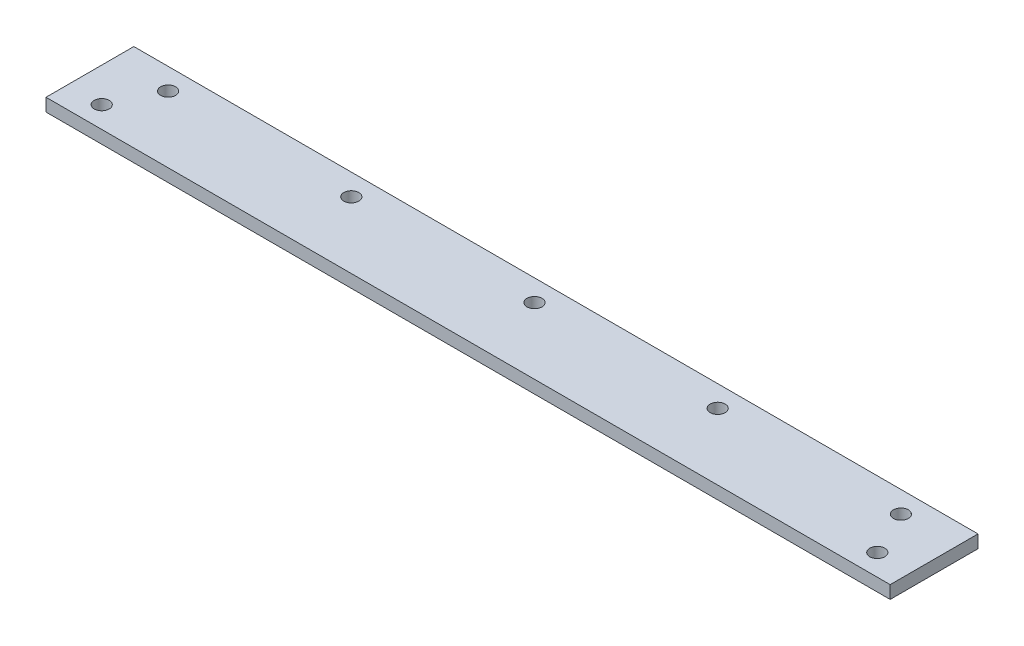
SolidWorks part; units mm, degrees
ref_plane "前视基准面" through (0, 0, 0) normal (0, 0, 1) x (1, 0, 0)
ref_plane "上视基准面" through (0, 0, 0) normal (0, 1, 0) x (1, 0, 0)
ref_plane "右视基准面" through (0, 0, 0) normal (1, 0, 0) x (0, 0, -1)
sketch "草图1" plane through (0, 0, 0) normal (0, 1, 0) x (1, 0, 0)
  line L1 (0, 0) -> (197, 0)
  line L2 (0, 0) -> (0, 20.5)
  line L3 (0, 20.5) -> (197, 20.5)
  line L4 (197, 0) -> (197, 20.5)
  dimension "D1" = 197
  dimension "D2" = 20.5
extrude "凸台-拉伸1" add sketch "草图1" along normal blind 3
sketch "草图2" plane through (0, 3, 0) normal (0, 1, 0) x (1, 0, 0)
  line L0 (13, 10) -> (3, 10)
  line L1 (0, 0) -> (13, 0)
  line L2 (0, 0) -> (0, 10)
  line L3 (0, 10) -> (13, 10)
  line L4 (13, 0) -> (13, 10)
  line L5 (197, 0) -> (184, 0)
  line L6 (197, 0) -> (197, 10)
  line L7 (197, 10) -> (184, 10)
  line L8 (184, 0) -> (184, 10)
  line L9 (3, 10) -> (13, 0)
  line L10 (184, 10) -> (194, 10)
  line L11 (194, 10) -> (184, 0)
  dimension "D1" = 13
  dimension "D2" = 13
  dimension "D3" = 10
  dimension "D4" = 10
  dimension "D5" = 10
  dimension "D6" = 10
sketch "草图3" plane through (0, 3, 0) normal (0, 1, 0) x (1, 0, 0)
  line L0 (3, 10) -> (13, 0) construction
  line L1 (194, 10) -> (184, 0) construction
  point P0 (8, 5)
  point P4 (189, 5)
hole_wizard "孔1" positions "草图3" profile "草图4" legacy end condition through all
sketch "草图4" plane through (8, 3, -5) normal (1, 0, 0) x (0, 0, 1)
  line L0 (0, 0) -> (0, 3)
  line L1 (0, 3) -> (1.75, 3)
  line L2 (1.75, 3) -> (1.75, 0)
  line L3 (1.75, 0) -> (0, 0)
  line L4 (0, 110) -> (0, -10) construction
  dimension "直径" = 3.5
  dimension "深度" = 3
sketch "草图5" plane through (0, 3, 0) normal (0, 1, 0) x (1, 0, 0)
  line L0 (13, 10) -> (13, 20.5)
  line L2 (197, 20.5) -> (0, 20.5) construction
  line L3 (184, 10) -> (184, 20.5)
  line L9 (13, 20.5) -> (184, 20.5)
  line L11 (13, 20.5) -> (13, 15.5)
  line L12 (13, 15.5) -> (184, 15.5)
  line L13 (184, 20.5) -> (184, 15.5)
  point P2 (98.5, 15.5)
  point P7 (55.75, 15.5)
  point P10 (141.25, 15.5)
  dimension "D1" = 5
  dimension "D2" = 42.75
  dimension "D3" = 42.75
sketch "草图6" plane through (0, 3, 0) normal (0, 1, 0) x (1, 0, 0)
  point P0 (98.5, 15.5)
  point P3 (141.25, 15.5)
  point P6 (55.75, 15.5)
  point P9 (13, 15.5)
  point P12 (184, 15.5)
hole_wizard "孔2" positions "草图6" profile "草图7" legacy end condition through all
sketch "草图7" plane through (98.5, 3, -15.5) normal (1, 0, 0) x (0, 0, 1)
  line L0 (0, 0) -> (0, 3)
  line L1 (0, 3) -> (1.75, 3)
  line L2 (1.75, 3) -> (1.75, 0)
  line L3 (1.75, 0) -> (0, 0)
  line L4 (0, 110) -> (0, -10) construction
  dimension "直径" = 3.5
  dimension "深度" = 3
